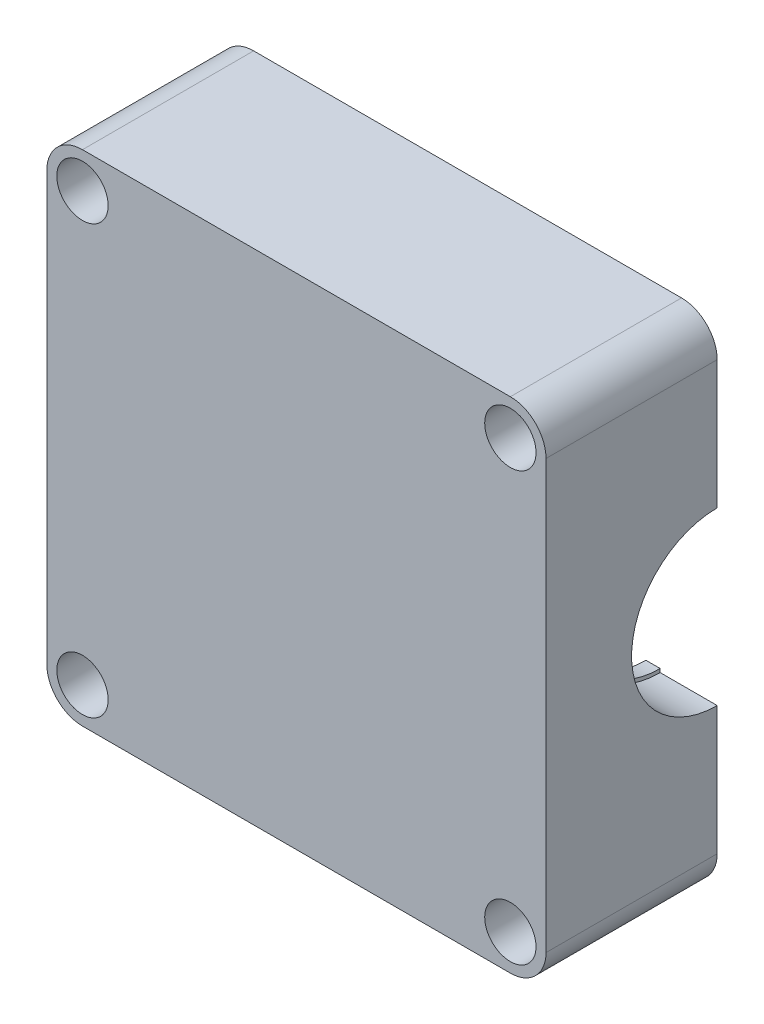
SolidWorks part; units mm, degrees
ref_plane "前视基准面" through (0, 0, 0) normal (0, 0, 1) x (1, 0, 0)
ref_plane "上视基准面" through (0, 0, 0) normal (0, 1, 0) x (1, 0, 0)
ref_plane "右视基准面" through (0, 0, 0) normal (1, 0, 0) x (0, 0, -1)
other "Configuration Table"
sketch "草图1" plane through (0, 0, 0) normal (0, 0, 1) x (-1, 0, 0)
  line L8 (-17.5, 15) -> (-17.5, -15)
  line L9 (-15, -17.5) -> (15, -17.5)
  line L10 (17.5, -15) -> (17.5, 15)
  line L11 (15, 17.5) -> (-15, 17.5)
  line L16 (15.6047, -11.417) -> (15.6047, 11.417)
  line L17 (-11.417, -15.6047) -> (11.417, -15.6047)
  line L18 (-15.6047, 11.417) -> (-15.6047, -11.417)
  line L19 (11.417, 15.6047) -> (-11.417, 15.6047)
  circle A2 centre (-15, -15) radius 1.8
  arc A8 (-15, 17.5) -> (-17.5, 15) centre (-15, 15) ccw
  arc A9 (-17.5, -15) -> (-15, -17.5) centre (-15, -15) ccw
  arc A10 (15, -17.5) -> (17.5, -15) centre (15, -15) ccw
  arc A11 (17.5, 15) -> (15, 17.5) centre (15, 15) ccw
  circle A12 centre (15, -15) radius 1.8
  circle A14 centre (15, 15) radius 1.8
  circle A16 centre (-15, 15) radius 1.8
  arc A38 (12.411, 14.7144) -> (14.7144, 12.411) centre (15, 15) ccw
  arc A39 (15.6047, 11.417) -> (14.7144, 12.411) centre (14.6048, 11.4171) ccw
  arc A40 (14.7144, -12.411) -> (15.6047, -11.417) centre (14.6048, -11.4171) ccw
  arc A41 (14.7144, -12.411) -> (12.411, -14.7144) centre (15, -15) ccw
  arc A42 (11.417, -15.6047) -> (12.411, -14.7144) centre (11.4171, -14.6048) ccw
  arc A43 (-12.411, -14.7144) -> (-11.417, -15.6047) centre (-11.4171, -14.6048) ccw
  arc A44 (-12.411, -14.7144) -> (-14.7144, -12.411) centre (-15, -15) ccw
  arc A45 (-15.6047, -11.417) -> (-14.7144, -12.411) centre (-14.6048, -11.4171) ccw
  arc A46 (-14.7144, 12.411) -> (-15.6047, 11.417) centre (-14.6048, 11.4171) ccw
  arc A47 (-14.7144, 12.411) -> (-12.411, 14.7144) centre (-15, 15) ccw
  arc A48 (-11.417, 15.6047) -> (-12.411, 14.7144) centre (-11.4171, 14.6048) ccw
  arc A49 (12.411, 14.7144) -> (11.417, 15.6047) centre (11.4171, 14.6048) ccw
extrude "凸台-拉伸1" add sketch "草图1" along normal blind 42
sketch "草图2" plane through (0, 17.5, 0) normal (0, 1, 0) x (1, 0, 0)
  line L0 (0, 0) -> (0, -12)
  circle A0 centre (0, -12) radius 6
  dimension "D2" = 12
  dimension "D1" = 12
extrude "切除-拉伸1" cut sketch "草图2" against normal through all
sketch "草图3" plane through (-17.5, 0, 0) normal (-1, 0, 0) x (0, 0, 1)
  line L0 (0, 0) -> (30, 0)
  circle A0 centre (30, 0) radius 6
  dimension "D2" = 12
  dimension "D1" = 30
extrude "切除-拉伸2" cut sketch "草图3" against normal through all
sketch "草图4" plane through (17.5, 0, 0) normal (1, 0, 0) x (0, 0, -1)
  line L0 (-30, 6) -> (-30, -18.5786)
  line L1 (-30, -18.5786) -> (7.9371, -18.5786)
  line L2 (7.9371, -18.5786) -> (5.1336, 19.1013)
  line L3 (5.1336, 19.1013) -> (-30, 19.1013)
  line L4 (-30, 19.1013) -> (-30, 6)
  circle A0 centre (-30, 0) radius 6 construction
extrude "切除-拉伸3" cut sketch "草图4" against normal through all contours L4 L0 L1 L2 L3
sketch "草图5" plane through (-15.6047, 0, 0) normal (1, 0, 0) x (0, 0, -1)
  line L0 (-30, -6.5) -> (-30, -6)
  line L1 (-30, 6) -> (-30, 6.5)
  arc A0 (-30, 6) -> (-30, -6) centre (-30, 0) ccw
  arc A1 (-30, 6.5) -> (-30, -6.5) centre (-30, 0) ccw
  dimension "D1" = 12
  dimension "D2" = 13
extrude "凸台-拉伸2" add sketch "草图5" along normal blind 2.1
sketch "草图6" plane through (-13.5047, 0, 0) normal (1, 0, 0) x (0, 0, -1)
  line L0 (-30, -6.5) -> (-30, -5.75)
  line L1 (-30, 5.75) -> (-30, 6.5)
  arc A0 (-30, 6.5) -> (-30, -6.5) centre (-30, 0) ccw
  arc A1 (-30, 5.75) -> (-30, -5.75) centre (-30, 0) ccw
  dimension "D1" = 13
  dimension "D2" = 11.5
extrude "凸台-拉伸3" add sketch "草图6" along normal blind 1
ref_plane "基准面1" through (0, 0, 0) normal (1, 0, 0) x (0, 0, -1)
mirror "镜向1" about plane through (0, 0, 0) normal (1, 0, 0) of "凸台-拉伸3", "凸台-拉伸2"
sketch "草图7" plane through (0, 0, 42) normal (0, 0, 1) x (1, 0, 0)
  line L0 (-15.6047, 11.417) -> (-15.6047, -11.417) construction
  line L1 (-11.417, -15.6047) -> (11.417, -15.6047) construction
  line L2 (15.6047, -11.417) -> (15.6047, 11.417) construction
  line L3 (11.417, 15.6047) -> (-11.417, 15.6047) construction
  line L12 (-15.6047, 11.417) -> (-15.6047, -11.417)
  line L13 (-11.417, -15.6047) -> (11.417, -15.6047)
  line L14 (15.6047, -11.417) -> (15.6047, 11.417)
  line L15 (11.417, 15.6047) -> (-11.417, 15.6047)
  line L16 (0, 0) -> (5, 0) construction
  line L17 (5, 0) -> (5, -5) construction
  line L18 (5, -5) -> (-5, -5) construction
  line L19 (-5, -5) -> (-5, 5) construction
  line L20 (-5, 5) -> (5, 5) construction
  line L21 (5, 5) -> (5, 0) construction
  arc A0 (-14.7144, 12.411) -> (-15.6047, 11.417) centre (-14.6048, 11.4171) ccw construction
  arc A1 (-15.6047, -11.417) -> (-14.7144, -12.411) centre (-14.6048, -11.4171) ccw construction
  arc A2 (-12.411, -14.7144) -> (-14.7144, -12.411) centre (-15, -15) ccw construction
  arc A3 (-12.411, -14.7144) -> (-11.417, -15.6047) centre (-11.4171, -14.6048) ccw construction
  arc A12 (11.417, -15.6047) -> (12.411, -14.7144) centre (11.4171, -14.6048) ccw construction
  arc A13 (14.7144, -12.411) -> (12.411, -14.7144) centre (15, -15) ccw construction
  arc A14 (14.7144, -12.411) -> (15.6047, -11.417) centre (14.6048, -11.4171) ccw construction
  arc A15 (15.6047, 11.417) -> (14.7144, 12.411) centre (14.6048, 11.4171) ccw construction
  arc A16 (12.411, 14.7144) -> (14.7144, 12.411) centre (15, 15) ccw construction
  arc A17 (12.411, 14.7144) -> (11.417, 15.6047) centre (11.4171, 14.6048) ccw construction
  arc A18 (-11.417, 15.6047) -> (-12.411, 14.7144) centre (-11.4171, 14.6048) ccw construction
  arc A19 (-14.7144, 12.411) -> (-12.411, 14.7144) centre (-15, 15) ccw construction
  arc A20 (-14.7144, 12.411) -> (-15.6047, 11.417) centre (-14.6048, 11.4171) ccw
  arc A21 (-15.6047, -11.417) -> (-14.7144, -12.411) centre (-14.6048, -11.4171) ccw
  arc A22 (-12.411, -14.7144) -> (-14.7144, -12.411) centre (-15, -15) ccw
  arc A23 (-12.411, -14.7144) -> (-11.417, -15.6047) centre (-11.4171, -14.6048) ccw
  arc A24 (11.417, -15.6047) -> (12.411, -14.7144) centre (11.4171, -14.6048) ccw
  arc A25 (14.7144, -12.411) -> (12.411, -14.7144) centre (15, -15) ccw
  arc A26 (14.7144, -12.411) -> (15.6047, -11.417) centre (14.6048, -11.4171) ccw
  arc A27 (15.6047, 11.417) -> (14.7144, 12.411) centre (14.6048, 11.4171) ccw
  arc A28 (12.411, 14.7144) -> (14.7144, 12.411) centre (15, 15) ccw
  arc A29 (12.411, 14.7144) -> (11.417, 15.6047) centre (11.4171, 14.6048) ccw
  arc A30 (-11.417, 15.6047) -> (-12.411, 14.7144) centre (-11.4171, 14.6048) ccw
  arc A31 (-14.7144, 12.411) -> (-12.411, 14.7144) centre (-15, 15) ccw
  dimension "D1" = 5
  dimension "D2" = 5
  dimension "D3" = 10
  dimension "D4" = 10
  dimension "D5" = 10
extrude "凸台-拉伸4" add sketch "草图7" against normal blind 2
sketch "草图8" plane through (0, -17.5, 0) normal (0, -1, 0) x (1, 0, 0)
  circle A0 centre (10.5, 33.5) radius 1.5031
  circle A1 centre (-10.5, 33.5) radius 1.5
extrude "切除-拉伸4" cut sketch "草图8" against normal blind 3
